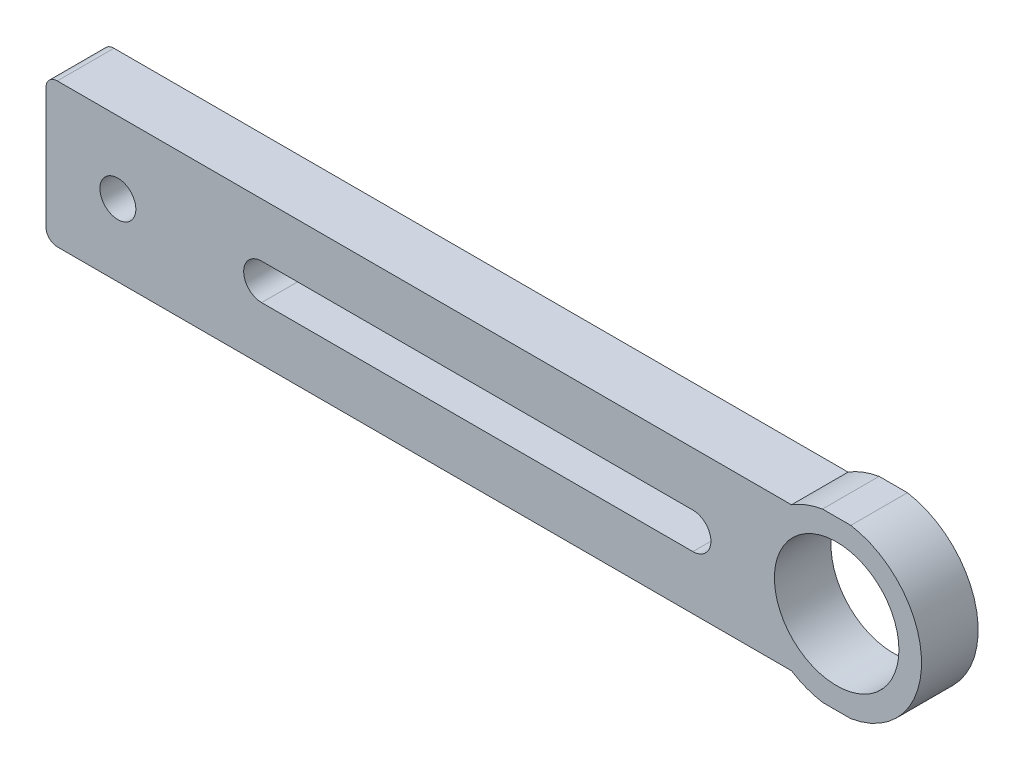
SolidWorks part; units mm, degrees
ref_plane "Front Plane" through (0, 0, 0) normal (0, 0, 1) x (1, 0, 0)
ref_plane "Top Plane" through (0, 0, 0) normal (0, 1, 0) x (1, 0, 0)
ref_plane "Right Plane" through (0, 0, 0) normal (1, 0, 0) x (0, 0, -1)
sketch "Sketch1" plane through (0, 0, 0) normal (0, 0, 1) x (1, 0, 0)
  line L0 (-57.15, 0) -> (-69.85, 0) construction
  line L2 (-69.85, -12.7) -> (-69.85, 12.7)
  line L5 (-69.85, -12.7) -> (69.85, 12.7) construction
  line L6 (-69.85, 12.7) -> (69.85, -12.7) construction
  line L7 (69.85, 12.7) -> (69.85, -12.7) construction
  line L12 (67.35, 14.7902) -> (72.35, 14.7902)
  line L18 (67.35, -14.7902) -> (72.35, -14.7902)
  line L19 (-57.15, 0) -> (-31.75, 0) construction
  line L20 (69.85, -12.7) -> (-69.85, -12.7) construction
  line L21 (69.85, 12.7) -> (-69.85, 12.7) construction
  line L23 (69.85, 14.7902) -> (69.85, -14.7902) construction
  line L25 (61.8681, 12.7) -> (-69.85, 12.7)
  line L26 (61.8681, -12.7) -> (-69.85, -12.7)
  line L27 (-31.75, 0) -> (44.45, 0) construction
  line L28 (-31.75, 3.175) -> (44.45, 3.175)
  line L29 (-31.75, -3.175) -> (44.45, -3.175)
  circle A0 centre (-57.15, 0) radius 3.175
  circle A6 centre (69.85, 0) radius 11
  circle A13 centre (69.85, 0) radius 15 construction
  arc A15 (72.35, -14.7902) -> (72.35, 14.7902) centre (69.85, 0) ccw
  arc A16 (67.35, 14.7902) -> (61.8681, 12.7) centre (69.85, 0) ccw
  arc A17 (67.35, -14.7902) -> (61.8681, -12.7) centre (69.85, 0) cw
  arc A18 (-31.75, 3.175) -> (-31.75, -3.175) centre (-31.75, 0) ccw
  arc A19 (44.45, -3.175) -> (44.45, 3.175) centre (44.45, 0) ccw
  point P0 (0, 0)
  point P20 (6.35, 0)
  point P26 (0, 0)
  point P27 (0, 0)
  dimension "D4" = 6.35
  dimension "D7" = 6.35
  dimension "D8" = 22
  dimension "D5" = 4
  dimension "D6" = 5
  dimension "D2" = 101.6
  dimension "D3" = 12.7
  dimension "D9" = 76.2
  dimension "D12" = 25.4
  dimension "D13" = 25.4
extrude "Boss-Extrude1" add sketch "Sketch1" along normal blind 10
fillet "Fillet3" radius 2 2 edges at (-69.85, -12.7, 5) (-69.85, 12.7, 5)
